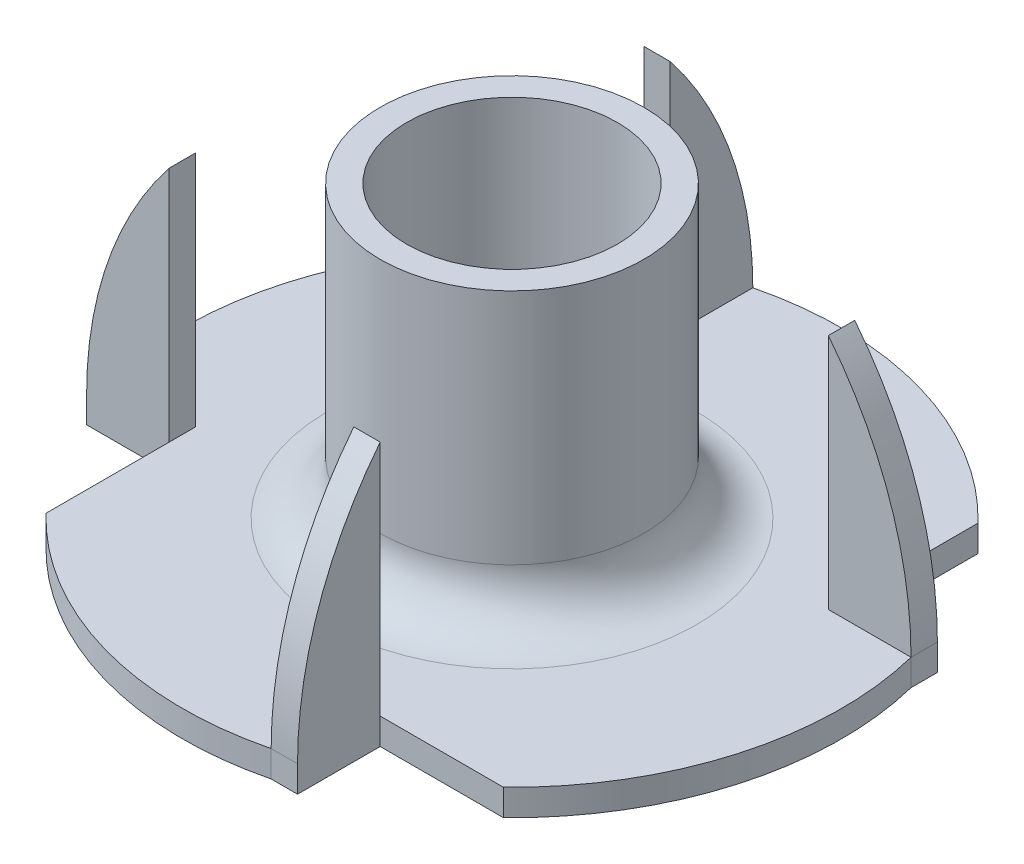
SolidWorks part; units mm, degrees
ref_plane "Front Plane" through (0, 0, 0) normal (0, 0, 1) x (1, 0, 0)
ref_plane "Top Plane" through (0, 0, 0) normal (0, 1, 0) x (1, 0, 0)
ref_plane "Right Plane" through (0, 0, 0) normal (1, 0, 0) x (0, 0, -1)
sketch "Sketch1" plane through (0, 0, 0) normal (1, 0, 0) x (0, 0, -1)
  line L0 (0, 6.9665) -> (0, -7.5331) construction
  line L1 (4, 12) -> (4, 3)
  line L2 (5, 12) -> (5, 3)
  line L3 (7, 1) -> (12.5, 1)
  line L4 (7, 0) -> (12.5, 0)
  line L5 (4, 12) -> (5, 12)
  line L6 (12.5, 1) -> (12.5, 0)
  arc A0 (4, 3) -> (7, 0) centre (7, 3) ccw
  arc A1 (5, 3) -> (7, 1) centre (7, 3) ccw
  point P1 (7, 1.5666)
  point P14 (0, 0)
  dimension "D1" = 3
  dimension "D2" = 2
  dimension "D4" = 12.5
  dimension "D7" = 4
  dimension "D3" = 1
  dimension "D5" = 12
  dimension "D6" = 1
revolve "Revolve1" add sketch "Sketch1" angle 360 about L0
sketch "Sketch5" plane through (0, 0, 0) normal (0, 1, 0) x (1, 0, 0)
  line L0 (12.1347, 3) -> (9, 3)
  line L1 (9, 3) -> (9, 8.6747)
  line L2 (3, -12.1347) -> (3, -9)
  line L3 (3, -9) -> (8.6747, -9)
  line L4 (-12.1347, -3) -> (-9, -3)
  line L5 (-9, -3) -> (-9, -8.6747)
  line L6 (-3, 12.1347) -> (-3, 9)
  line L7 (-3, 9) -> (-8.6747, 9)
  circle A0 centre (0, 0) radius 12.5 construction
  arc A1 (9, 8.6747) -> (12.1347, 3) centre (0, 0) cw
  arc A2 (8.6747, -9) -> (3, -12.1347) centre (0, 0) cw
  arc A3 (-9, -8.6747) -> (-12.1347, -3) centre (0, 0) cw
  arc A4 (-8.6747, 9) -> (-3, 12.1347) centre (0, 0) cw
  point P18 (0, 0)
  dimension "D1" = 12.5
  dimension "D2" = 9
  dimension "D3" = 3
  dimension "D4" = 4
extrude "Cut-Extrude2" cut sketch "Sketch5" along normal blind 1
sketch "Sketch6" plane through (0, 0, 3) normal (0, 0, 1) x (1, 0, 0)
  line L0 (-9, 0) -> (-9, 10)
  line L1 (-9, 0) -> (-12.1347, 0)
  line L2 (-12.1347, 0) -> (-12.1347, 1)
  line L3 (-9, 1) -> (-12.1347, 1) construction
  arc A0 (-12.1347, 1) -> (-9, 10) centre (2.3527, 1) cw
  dimension "D1" = 9
extrude "Boss-Extrude2" add sketch "Sketch6" along normal blind 1
sketch "Sketch7" plane through (0, 0, 0) normal (0, 0, 1) x (1, 0, 0)
  line L0 (0, -4.2752) -> (0, -2.857) construction
pattern_circular "CirPattern2" count 4 over 360 about axis through (0, 0, 0) along (0, 1, 0) of "Boss-Extrude2"
